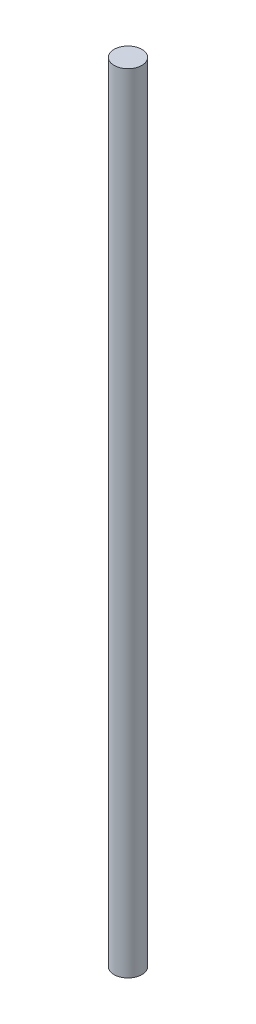
SolidWorks part; units mm, degrees
ref_plane "Front Plane" through (0, 0, 0) normal (1, 0, 0) x (0, 1, 0)
ref_plane "Top Plane" through (0, 0, 0) normal (0, 0, 1) x (0, 1, 0)
ref_plane "Right Plane" through (0, 0, 0) normal (0, 1, 0) x (-1, 0, 0)
sketch "Sketch1" plane through (0, 0, 0) normal (0, 1, 0) x (-1, 0, 0)
  circle A0 centre (0, 0) radius 21.082
  dimension "D1" = 42.164
extrude "Boss-Extrude1" add sketch "Sketch1" along normal mid plane 1193.8
